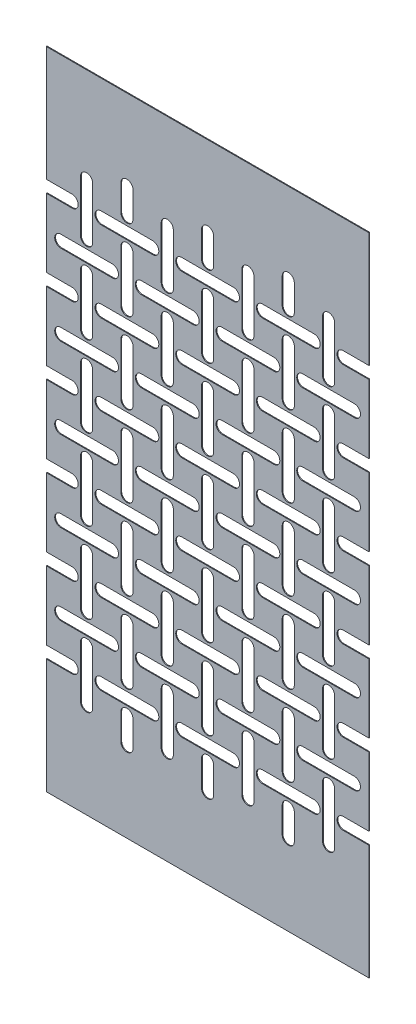
SolidWorks part; units mm, degrees
material "Kapton"
ref_plane "Front Plane" through (0, 0, 0) normal (0, 0, 1) x (1, 0, 0)
ref_plane "Top Plane" through (0, 0, 0) normal (0, 1, 0) x (1, 0, 0)
ref_plane "Right Plane" through (0, 0, 0) normal (1, 0, 0) x (0, 0, -1)
sketch "Model" plane through (0, 0, 0) normal (0, 0, 1) x (1, 0, 0)
  line L0 (0, 31.5) -> (6.4031, 31.5)
  line L1 (0, 28.5) -> (6.4031, 28.5)
  line L2 (13.5969, 31.5) -> (26.4031, 31.5)
  line L3 (13.5969, 28.5) -> (26.4031, 28.5)
  line L4 (33.5969, 31.5) -> (46.4031, 31.5)
  line L5 (33.5969, 28.5) -> (46.4031, 28.5)
  line L6 (53.5969, 31.5) -> (66.4031, 31.5)
  line L7 (53.5969, 28.5) -> (66.4031, 28.5)
  line L8 (73.5969, 31.5) -> (80, 31.5)
  line L9 (73.5969, 28.5) -> (80, 28.5)
  line L10 (3.5969, 41.5) -> (16.4031, 41.5)
  line L11 (3.5969, 38.5) -> (16.4031, 38.5)
  line L12 (23.5969, 41.5) -> (36.4031, 41.5)
  line L13 (23.5969, 38.5) -> (36.4031, 38.5)
  line L14 (43.5969, 41.5) -> (56.4031, 41.5)
  line L15 (43.5969, 38.5) -> (56.4031, 38.5)
  line L16 (63.5969, 41.5) -> (76.4031, 41.5)
  line L17 (63.5969, 38.5) -> (76.4031, 38.5)
  line L18 (0, 51.5) -> (6.4031, 51.5)
  line L19 (0, 48.5) -> (6.4031, 48.5)
  line L20 (13.5969, 51.5) -> (26.4031, 51.5)
  line L21 (13.5969, 48.5) -> (26.4031, 48.5)
  line L22 (33.5969, 51.5) -> (46.4031, 51.5)
  line L23 (33.5969, 48.5) -> (46.4031, 48.5)
  line L24 (53.5969, 51.5) -> (66.4031, 51.5)
  line L25 (53.5969, 48.5) -> (66.4031, 48.5)
  line L26 (73.5969, 51.5) -> (80, 51.5)
  line L27 (73.5969, 48.5) -> (80, 48.5)
  line L28 (3.5969, 61.5) -> (16.4031, 61.5)
  line L29 (3.5969, 58.5) -> (16.4031, 58.5)
  line L30 (23.5969, 61.5) -> (36.4031, 61.5)
  line L31 (23.5969, 58.5) -> (36.4031, 58.5)
  line L32 (43.5969, 61.5) -> (56.4031, 61.5)
  line L33 (43.5969, 58.5) -> (56.4031, 58.5)
  line L34 (63.5969, 61.5) -> (76.4031, 61.5)
  line L35 (63.5969, 58.5) -> (76.4031, 58.5)
  line L36 (0, 71.5) -> (6.4031, 71.5)
  line L37 (0, 68.5) -> (6.4031, 68.5)
  line L38 (13.5969, 71.5) -> (26.4031, 71.5)
  line L39 (13.5969, 68.5) -> (26.4031, 68.5)
  line L40 (33.5969, 71.5) -> (46.4031, 71.5)
  line L41 (33.5969, 68.5) -> (46.4031, 68.5)
  line L42 (53.5969, 71.5) -> (66.4031, 71.5)
  line L43 (53.5969, 68.5) -> (66.4031, 68.5)
  line L44 (73.5969, 71.5) -> (80, 71.5)
  line L45 (73.5969, 68.5) -> (80, 68.5)
  line L46 (3.5969, 81.5) -> (16.4031, 81.5)
  line L47 (3.5969, 78.5) -> (16.4031, 78.5)
  line L48 (23.5969, 81.5) -> (36.4031, 81.5)
  line L49 (23.5969, 78.5) -> (36.4031, 78.5)
  line L50 (43.5969, 81.5) -> (56.4031, 81.5)
  line L51 (43.5969, 78.5) -> (56.4031, 78.5)
  line L52 (63.5969, 81.5) -> (76.4031, 81.5)
  line L53 (63.5969, 78.5) -> (76.4031, 78.5)
  line L54 (0, 91.5) -> (6.4031, 91.5)
  line L55 (0, 88.5) -> (6.4031, 88.5)
  line L56 (13.5969, 91.5) -> (26.4031, 91.5)
  line L57 (13.5969, 88.5) -> (26.4031, 88.5)
  line L58 (33.5969, 91.5) -> (46.4031, 91.5)
  line L59 (33.5969, 88.5) -> (46.4031, 88.5)
  line L60 (53.5969, 91.5) -> (66.4031, 91.5)
  line L61 (53.5969, 88.5) -> (66.4031, 88.5)
  line L62 (73.5969, 91.5) -> (80, 91.5)
  line L63 (73.5969, 88.5) -> (80, 88.5)
  line L64 (3.5969, 101.5) -> (16.4031, 101.5)
  line L65 (3.5969, 98.5) -> (16.4031, 98.5)
  line L66 (23.5969, 101.5) -> (36.4031, 101.5)
  line L67 (23.5969, 98.5) -> (36.4031, 98.5)
  line L68 (43.5969, 101.5) -> (56.4031, 101.5)
  line L69 (43.5969, 98.5) -> (56.4031, 98.5)
  line L70 (63.5969, 101.5) -> (76.4031, 101.5)
  line L71 (63.5969, 98.5) -> (76.4031, 98.5)
  line L72 (0, 111.5) -> (6.4031, 111.5)
  line L73 (0, 108.5) -> (6.4031, 108.5)
  line L74 (13.5969, 111.5) -> (26.4031, 111.5)
  line L75 (13.5969, 108.5) -> (26.4031, 108.5)
  line L76 (33.5969, 111.5) -> (46.4031, 111.5)
  line L77 (33.5969, 108.5) -> (46.4031, 108.5)
  line L78 (53.5969, 111.5) -> (66.4031, 111.5)
  line L79 (53.5969, 108.5) -> (66.4031, 108.5)
  line L80 (73.5969, 111.5) -> (80, 111.5)
  line L81 (73.5969, 108.5) -> (80, 108.5)
  line L82 (3.5969, 121.5) -> (16.4031, 121.5)
  line L83 (3.5969, 118.5) -> (16.4031, 118.5)
  line L84 (23.5969, 121.5) -> (36.4031, 121.5)
  line L85 (23.5969, 118.5) -> (36.4031, 118.5)
  line L86 (43.5969, 121.5) -> (56.4031, 121.5)
  line L87 (43.5969, 118.5) -> (56.4031, 118.5)
  line L88 (63.5969, 121.5) -> (76.4031, 121.5)
  line L89 (63.5969, 118.5) -> (76.4031, 118.5)
  line L90 (0, 131.5) -> (6.4031, 131.5)
  line L91 (0, 128.5) -> (6.4031, 128.5)
  line L92 (13.5969, 131.5) -> (26.4031, 131.5)
  line L93 (13.5969, 128.5) -> (26.4031, 128.5)
  line L94 (33.5969, 131.5) -> (46.4031, 131.5)
  line L95 (33.5969, 128.5) -> (46.4031, 128.5)
  line L96 (53.5969, 131.5) -> (66.4031, 131.5)
  line L97 (53.5969, 128.5) -> (66.4031, 128.5)
  line L98 (73.5969, 131.5) -> (80, 131.5)
  line L99 (73.5969, 128.5) -> (80, 128.5)
  line L100 (11.5, 23.5969) -> (11.5, 36.4031)
  line L101 (8.5, 23.5969) -> (8.5, 36.4031)
  line L102 (11.5, 43.5969) -> (11.5, 56.4031)
  line L103 (8.5, 43.5969) -> (8.5, 56.4031)
  line L104 (11.5, 63.5969) -> (11.5, 76.4031)
  line L105 (8.5, 63.5969) -> (8.5, 76.4031)
  line L106 (11.5, 83.5969) -> (11.5, 96.4031)
  line L107 (8.5, 83.5969) -> (8.5, 96.4031)
  line L108 (11.5, 103.5969) -> (11.5, 116.4031)
  line L109 (8.5, 103.5969) -> (8.5, 116.4031)
  line L110 (11.5, 123.5969) -> (11.5, 136.4031)
  line L111 (8.5, 123.5969) -> (8.5, 136.4031)
  line L112 (21.5, 20) -> (21.5, 26.4031)
  line L113 (18.5, 20) -> (18.5, 26.4031)
  line L114 (21.5, 33.5969) -> (21.5, 46.4031)
  line L115 (18.5, 33.5969) -> (18.5, 46.4031)
  line L116 (21.5, 53.5969) -> (21.5, 66.4031)
  line L117 (18.5, 53.5969) -> (18.5, 66.4031)
  line L118 (21.5, 73.5969) -> (21.5, 86.4031)
  line L119 (18.5, 73.5969) -> (18.5, 86.4031)
  line L120 (21.5, 93.5969) -> (21.5, 106.4031)
  line L121 (18.5, 93.5969) -> (18.5, 106.4031)
  line L122 (21.5, 113.5969) -> (21.5, 126.4031)
  line L123 (18.5, 113.5969) -> (18.5, 126.4031)
  line L124 (21.5, 133.5969) -> (21.5, 140)
  line L125 (18.5, 133.5969) -> (18.5, 140)
  line L126 (31.5, 23.5969) -> (31.5, 36.4031)
  line L127 (28.5, 23.5969) -> (28.5, 36.4031)
  line L128 (31.5, 43.5969) -> (31.5, 56.4031)
  line L129 (28.5, 43.5969) -> (28.5, 56.4031)
  line L130 (31.5, 63.5969) -> (31.5, 76.4031)
  line L131 (28.5, 63.5969) -> (28.5, 76.4031)
  line L132 (31.5, 83.5969) -> (31.5, 96.4031)
  line L133 (28.5, 83.5969) -> (28.5, 96.4031)
  line L134 (31.5, 103.5969) -> (31.5, 116.4031)
  line L135 (28.5, 103.5969) -> (28.5, 116.4031)
  line L136 (31.5, 123.5969) -> (31.5, 136.4031)
  line L137 (28.5, 123.5969) -> (28.5, 136.4031)
  line L138 (41.5, 20) -> (41.5, 26.4031)
  line L139 (38.5, 20) -> (38.5, 26.4031)
  line L140 (41.5, 33.5969) -> (41.5, 46.4031)
  line L141 (38.5, 33.5969) -> (38.5, 46.4031)
  line L142 (41.5, 53.5969) -> (41.5, 66.4031)
  line L143 (38.5, 53.5969) -> (38.5, 66.4031)
  line L144 (41.5, 73.5969) -> (41.5, 86.4031)
  line L145 (38.5, 73.5969) -> (38.5, 86.4031)
  line L146 (41.5, 93.5969) -> (41.5, 106.4031)
  line L147 (38.5, 93.5969) -> (38.5, 106.4031)
  line L148 (41.5, 113.5969) -> (41.5, 126.4031)
  line L149 (38.5, 113.5969) -> (38.5, 126.4031)
  line L150 (41.5, 133.5969) -> (41.5, 140)
  line L151 (38.5, 133.5969) -> (38.5, 140)
  line L152 (51.5, 23.5969) -> (51.5, 36.4031)
  line L153 (48.5, 23.5969) -> (48.5, 36.4031)
  line L154 (51.5, 43.5969) -> (51.5, 56.4031)
  line L155 (48.5, 43.5969) -> (48.5, 56.4031)
  line L156 (51.5, 63.5969) -> (51.5, 76.4031)
  line L157 (48.5, 63.5969) -> (48.5, 76.4031)
  line L158 (51.5, 83.5969) -> (51.5, 96.4031)
  line L159 (48.5, 83.5969) -> (48.5, 96.4031)
  line L160 (51.5, 103.5969) -> (51.5, 116.4031)
  line L161 (48.5, 103.5969) -> (48.5, 116.4031)
  line L162 (51.5, 123.5969) -> (51.5, 136.4031)
  line L163 (48.5, 123.5969) -> (48.5, 136.4031)
  line L164 (61.5, 20) -> (61.5, 26.4031)
  line L165 (58.5, 20) -> (58.5, 26.4031)
  line L166 (61.5, 33.5969) -> (61.5, 46.4031)
  line L167 (58.5, 33.5969) -> (58.5, 46.4031)
  line L168 (61.5, 53.5969) -> (61.5, 66.4031)
  line L169 (58.5, 53.5969) -> (58.5, 66.4031)
  line L170 (61.5, 73.5969) -> (61.5, 86.4031)
  line L171 (58.5, 73.5969) -> (58.5, 86.4031)
  line L172 (61.5, 93.5969) -> (61.5, 106.4031)
  line L173 (58.5, 93.5969) -> (58.5, 106.4031)
  line L174 (61.5, 113.5969) -> (61.5, 126.4031)
  line L175 (58.5, 113.5969) -> (58.5, 126.4031)
  line L176 (61.5, 133.5969) -> (61.5, 140)
  line L177 (58.5, 133.5969) -> (58.5, 140)
  line L178 (71.5, 23.5969) -> (71.5, 36.4031)
  line L179 (68.5, 23.5969) -> (68.5, 36.4031)
  line L180 (71.5, 43.5969) -> (71.5, 56.4031)
  line L181 (68.5, 43.5969) -> (68.5, 56.4031)
  line L182 (71.5, 63.5969) -> (71.5, 76.4031)
  line L183 (68.5, 63.5969) -> (68.5, 76.4031)
  line L184 (71.5, 83.5969) -> (71.5, 96.4031)
  line L185 (68.5, 83.5969) -> (68.5, 96.4031)
  line L186 (71.5, 103.5969) -> (71.5, 116.4031)
  line L187 (68.5, 103.5969) -> (68.5, 116.4031)
  line L188 (71.5, 123.5969) -> (71.5, 136.4031)
  line L189 (68.5, 123.5969) -> (68.5, 136.4031)
  line L190 (0, 0) -> (80, 0)
  line L191 (80, 0) -> (80, 28.5)
  line L192 (80, 31.5) -> (80, 48.5)
  line L193 (80, 51.5) -> (80, 68.5)
  line L194 (80, 71.5) -> (80, 88.5)
  line L195 (80, 91.5) -> (80, 108.5)
  line L196 (80, 111.5) -> (80, 128.5)
  line L197 (80, 131.5) -> (80, 160)
  line L198 (80, 160) -> (0, 160)
  line L199 (0, 0) -> (0, 28.5)
  line L200 (0, 31.5) -> (0, 48.5)
  line L201 (0, 51.5) -> (0, 68.5)
  line L202 (0, 71.5) -> (0, 88.5)
  line L203 (0, 91.5) -> (0, 108.5)
  line L204 (0, 111.5) -> (0, 128.5)
  line L205 (0, 131.5) -> (0, 160)
  arc A0 (6.4031, 28.5) -> (6.4031, 31.5) centre (6.4031, 30) ccw
  arc A1 (13.5969, 31.5) -> (13.5969, 28.5) centre (13.5969, 30) ccw
  arc A2 (26.4031, 28.5) -> (26.4031, 31.5) centre (26.4031, 30) ccw
  arc A3 (33.5969, 31.5) -> (33.5969, 28.5) centre (33.5969, 30) ccw
  arc A4 (46.4031, 28.5) -> (46.4031, 31.5) centre (46.4031, 30) ccw
  arc A5 (53.5969, 31.5) -> (53.5969, 28.5) centre (53.5969, 30) ccw
  arc A6 (66.4031, 28.5) -> (66.4031, 31.5) centre (66.4031, 30) ccw
  arc A7 (73.5969, 31.5) -> (73.5969, 28.5) centre (73.5969, 30) ccw
  arc A8 (3.5969, 41.5) -> (3.5969, 38.5) centre (3.5969, 40) ccw
  arc A9 (16.4031, 38.5) -> (16.4031, 41.5) centre (16.4031, 40) ccw
  arc A10 (23.5969, 41.5) -> (23.5969, 38.5) centre (23.5969, 40) ccw
  arc A11 (36.4031, 38.5) -> (36.4031, 41.5) centre (36.4031, 40) ccw
  arc A12 (43.5969, 41.5) -> (43.5969, 38.5) centre (43.5969, 40) ccw
  arc A13 (56.4031, 38.5) -> (56.4031, 41.5) centre (56.4031, 40) ccw
  arc A14 (63.5969, 41.5) -> (63.5969, 38.5) centre (63.5969, 40) ccw
  arc A15 (76.4031, 38.5) -> (76.4031, 41.5) centre (76.4031, 40) ccw
  arc A16 (6.4031, 48.5) -> (6.4031, 51.5) centre (6.4031, 50) ccw
  arc A17 (13.5969, 51.5) -> (13.5969, 48.5) centre (13.5969, 50) ccw
  arc A18 (26.4031, 48.5) -> (26.4031, 51.5) centre (26.4031, 50) ccw
  arc A19 (33.5969, 51.5) -> (33.5969, 48.5) centre (33.5969, 50) ccw
  arc A20 (46.4031, 48.5) -> (46.4031, 51.5) centre (46.4031, 50) ccw
  arc A21 (53.5969, 51.5) -> (53.5969, 48.5) centre (53.5969, 50) ccw
  arc A22 (66.4031, 48.5) -> (66.4031, 51.5) centre (66.4031, 50) ccw
  arc A23 (73.5969, 51.5) -> (73.5969, 48.5) centre (73.5969, 50) ccw
  arc A24 (3.5969, 61.5) -> (3.5969, 58.5) centre (3.5969, 60) ccw
  arc A25 (16.4031, 58.5) -> (16.4031, 61.5) centre (16.4031, 60) ccw
  arc A26 (23.5969, 61.5) -> (23.5969, 58.5) centre (23.5969, 60) ccw
  arc A27 (36.4031, 58.5) -> (36.4031, 61.5) centre (36.4031, 60) ccw
  arc A28 (43.5969, 61.5) -> (43.5969, 58.5) centre (43.5969, 60) ccw
  arc A29 (56.4031, 58.5) -> (56.4031, 61.5) centre (56.4031, 60) ccw
  arc A30 (63.5969, 61.5) -> (63.5969, 58.5) centre (63.5969, 60) ccw
  arc A31 (76.4031, 58.5) -> (76.4031, 61.5) centre (76.4031, 60) ccw
  arc A32 (6.4031, 68.5) -> (6.4031, 71.5) centre (6.4031, 70) ccw
  arc A33 (13.5969, 71.5) -> (13.5969, 68.5) centre (13.5969, 70) ccw
  arc A34 (26.4031, 68.5) -> (26.4031, 71.5) centre (26.4031, 70) ccw
  arc A35 (33.5969, 71.5) -> (33.5969, 68.5) centre (33.5969, 70) ccw
  arc A36 (46.4031, 68.5) -> (46.4031, 71.5) centre (46.4031, 70) ccw
  arc A37 (53.5969, 71.5) -> (53.5969, 68.5) centre (53.5969, 70) ccw
  arc A38 (66.4031, 68.5) -> (66.4031, 71.5) centre (66.4031, 70) ccw
  arc A39 (73.5969, 71.5) -> (73.5969, 68.5) centre (73.5969, 70) ccw
  arc A40 (3.5969, 81.5) -> (3.5969, 78.5) centre (3.5969, 80) ccw
  arc A41 (16.4031, 78.5) -> (16.4031, 81.5) centre (16.4031, 80) ccw
  arc A42 (23.5969, 81.5) -> (23.5969, 78.5) centre (23.5969, 80) ccw
  arc A43 (36.4031, 78.5) -> (36.4031, 81.5) centre (36.4031, 80) ccw
  arc A44 (43.5969, 81.5) -> (43.5969, 78.5) centre (43.5969, 80) ccw
  arc A45 (56.4031, 78.5) -> (56.4031, 81.5) centre (56.4031, 80) ccw
  arc A46 (63.5969, 81.5) -> (63.5969, 78.5) centre (63.5969, 80) ccw
  arc A47 (76.4031, 78.5) -> (76.4031, 81.5) centre (76.4031, 80) ccw
  arc A48 (6.4031, 88.5) -> (6.4031, 91.5) centre (6.4031, 90) ccw
  arc A49 (13.5969, 91.5) -> (13.5969, 88.5) centre (13.5969, 90) ccw
  arc A50 (26.4031, 88.5) -> (26.4031, 91.5) centre (26.4031, 90) ccw
  arc A51 (33.5969, 91.5) -> (33.5969, 88.5) centre (33.5969, 90) ccw
  arc A52 (46.4031, 88.5) -> (46.4031, 91.5) centre (46.4031, 90) ccw
  arc A53 (53.5969, 91.5) -> (53.5969, 88.5) centre (53.5969, 90) ccw
  arc A54 (66.4031, 88.5) -> (66.4031, 91.5) centre (66.4031, 90) ccw
  arc A55 (73.5969, 91.5) -> (73.5969, 88.5) centre (73.5969, 90) ccw
  arc A56 (3.5969, 101.5) -> (3.5969, 98.5) centre (3.5969, 100) ccw
  arc A57 (16.4031, 98.5) -> (16.4031, 101.5) centre (16.4031, 100) ccw
  arc A58 (23.5969, 101.5) -> (23.5969, 98.5) centre (23.5969, 100) ccw
  arc A59 (36.4031, 98.5) -> (36.4031, 101.5) centre (36.4031, 100) ccw
  arc A60 (43.5969, 101.5) -> (43.5969, 98.5) centre (43.5969, 100) ccw
  arc A61 (56.4031, 98.5) -> (56.4031, 101.5) centre (56.4031, 100) ccw
  arc A62 (63.5969, 101.5) -> (63.5969, 98.5) centre (63.5969, 100) ccw
  arc A63 (76.4031, 98.5) -> (76.4031, 101.5) centre (76.4031, 100) ccw
  arc A64 (6.4031, 108.5) -> (6.4031, 111.5) centre (6.4031, 110) ccw
  arc A65 (13.5969, 111.5) -> (13.5969, 108.5) centre (13.5969, 110) ccw
  arc A66 (26.4031, 108.5) -> (26.4031, 111.5) centre (26.4031, 110) ccw
  arc A67 (33.5969, 111.5) -> (33.5969, 108.5) centre (33.5969, 110) ccw
  arc A68 (46.4031, 108.5) -> (46.4031, 111.5) centre (46.4031, 110) ccw
  arc A69 (53.5969, 111.5) -> (53.5969, 108.5) centre (53.5969, 110) ccw
  arc A70 (66.4031, 108.5) -> (66.4031, 111.5) centre (66.4031, 110) ccw
  arc A71 (73.5969, 111.5) -> (73.5969, 108.5) centre (73.5969, 110) ccw
  arc A72 (3.5969, 121.5) -> (3.5969, 118.5) centre (3.5969, 120) ccw
  arc A73 (16.4031, 118.5) -> (16.4031, 121.5) centre (16.4031, 120) ccw
  arc A74 (23.5969, 121.5) -> (23.5969, 118.5) centre (23.5969, 120) ccw
  arc A75 (36.4031, 118.5) -> (36.4031, 121.5) centre (36.4031, 120) ccw
  arc A76 (43.5969, 121.5) -> (43.5969, 118.5) centre (43.5969, 120) ccw
  arc A77 (56.4031, 118.5) -> (56.4031, 121.5) centre (56.4031, 120) ccw
  arc A78 (63.5969, 121.5) -> (63.5969, 118.5) centre (63.5969, 120) ccw
  arc A79 (76.4031, 118.5) -> (76.4031, 121.5) centre (76.4031, 120) ccw
  arc A80 (6.4031, 128.5) -> (6.4031, 131.5) centre (6.4031, 130) ccw
  arc A81 (13.5969, 131.5) -> (13.5969, 128.5) centre (13.5969, 130) ccw
  arc A82 (26.4031, 128.5) -> (26.4031, 131.5) centre (26.4031, 130) ccw
  arc A83 (33.5969, 131.5) -> (33.5969, 128.5) centre (33.5969, 130) ccw
  arc A84 (46.4031, 128.5) -> (46.4031, 131.5) centre (46.4031, 130) ccw
  arc A85 (53.5969, 131.5) -> (53.5969, 128.5) centre (53.5969, 130) ccw
  arc A86 (66.4031, 128.5) -> (66.4031, 131.5) centre (66.4031, 130) ccw
  arc A87 (73.5969, 131.5) -> (73.5969, 128.5) centre (73.5969, 130) ccw
  arc A88 (8.5, 23.5969) -> (11.5, 23.5969) centre (10, 23.5969) ccw
  arc A89 (11.5, 36.4031) -> (8.5, 36.4031) centre (10, 36.4031) ccw
  arc A90 (8.5, 43.5969) -> (11.5, 43.5969) centre (10, 43.5969) ccw
  arc A91 (11.5, 56.4031) -> (8.5, 56.4031) centre (10, 56.4031) ccw
  arc A92 (8.5, 63.5969) -> (11.5, 63.5969) centre (10, 63.5969) ccw
  arc A93 (11.5, 76.4031) -> (8.5, 76.4031) centre (10, 76.4031) ccw
  arc A94 (8.5, 83.5969) -> (11.5, 83.5969) centre (10, 83.5969) ccw
  arc A95 (11.5, 96.4031) -> (8.5, 96.4031) centre (10, 96.4031) ccw
  arc A96 (8.5, 103.5969) -> (11.5, 103.5969) centre (10, 103.5969) ccw
  arc A97 (11.5, 116.4031) -> (8.5, 116.4031) centre (10, 116.4031) ccw
  arc A98 (8.5, 123.5969) -> (11.5, 123.5969) centre (10, 123.5969) ccw
  arc A99 (11.5, 136.4031) -> (8.5, 136.4031) centre (10, 136.4031) ccw
  arc A100 (18.5, 20) -> (21.5, 20) centre (20, 20) ccw
  arc A101 (21.5, 26.4031) -> (18.5, 26.4031) centre (20, 26.4031) ccw
  arc A102 (18.5, 33.5969) -> (21.5, 33.5969) centre (20, 33.5969) ccw
  arc A103 (21.5, 46.4031) -> (18.5, 46.4031) centre (20, 46.4031) ccw
  arc A104 (18.5, 53.5969) -> (21.5, 53.5969) centre (20, 53.5969) ccw
  arc A105 (21.5, 66.4031) -> (18.5, 66.4031) centre (20, 66.4031) ccw
  arc A106 (18.5, 73.5969) -> (21.5, 73.5969) centre (20, 73.5969) ccw
  arc A107 (21.5, 86.4031) -> (18.5, 86.4031) centre (20, 86.4031) ccw
  arc A108 (18.5, 93.5969) -> (21.5, 93.5969) centre (20, 93.5969) ccw
  arc A109 (21.5, 106.4031) -> (18.5, 106.4031) centre (20, 106.4031) ccw
  arc A110 (18.5, 113.5969) -> (21.5, 113.5969) centre (20, 113.5969) ccw
  arc A111 (21.5, 126.4031) -> (18.5, 126.4031) centre (20, 126.4031) ccw
  arc A112 (18.5, 133.5969) -> (21.5, 133.5969) centre (20, 133.5969) ccw
  arc A113 (21.5, 140) -> (18.5, 140) centre (20, 140) ccw
  arc A114 (28.5, 23.5969) -> (31.5, 23.5969) centre (30, 23.5969) ccw
  arc A115 (31.5, 36.4031) -> (28.5, 36.4031) centre (30, 36.4031) ccw
  arc A116 (28.5, 43.5969) -> (31.5, 43.5969) centre (30, 43.5969) ccw
  arc A117 (31.5, 56.4031) -> (28.5, 56.4031) centre (30, 56.4031) ccw
  arc A118 (28.5, 63.5969) -> (31.5, 63.5969) centre (30, 63.5969) ccw
  arc A119 (31.5, 76.4031) -> (28.5, 76.4031) centre (30, 76.4031) ccw
  arc A120 (28.5, 83.5969) -> (31.5, 83.5969) centre (30, 83.5969) ccw
  arc A121 (31.5, 96.4031) -> (28.5, 96.4031) centre (30, 96.4031) ccw
  arc A122 (28.5, 103.5969) -> (31.5, 103.5969) centre (30, 103.5969) ccw
  arc A123 (31.5, 116.4031) -> (28.5, 116.4031) centre (30, 116.4031) ccw
  arc A124 (28.5, 123.5969) -> (31.5, 123.5969) centre (30, 123.5969) ccw
  arc A125 (31.5, 136.4031) -> (28.5, 136.4031) centre (30, 136.4031) ccw
  arc A126 (38.5, 20) -> (41.5, 20) centre (40, 20) ccw
  arc A127 (41.5, 26.4031) -> (38.5, 26.4031) centre (40, 26.4031) ccw
  arc A128 (38.5, 33.5969) -> (41.5, 33.5969) centre (40, 33.5969) ccw
  arc A129 (41.5, 46.4031) -> (38.5, 46.4031) centre (40, 46.4031) ccw
  arc A130 (38.5, 53.5969) -> (41.5, 53.5969) centre (40, 53.5969) ccw
  arc A131 (41.5, 66.4031) -> (38.5, 66.4031) centre (40, 66.4031) ccw
  arc A132 (38.5, 73.5969) -> (41.5, 73.5969) centre (40, 73.5969) ccw
  arc A133 (41.5, 86.4031) -> (38.5, 86.4031) centre (40, 86.4031) ccw
  arc A134 (38.5, 93.5969) -> (41.5, 93.5969) centre (40, 93.5969) ccw
  arc A135 (41.5, 106.4031) -> (38.5, 106.4031) centre (40, 106.4031) ccw
  arc A136 (38.5, 113.5969) -> (41.5, 113.5969) centre (40, 113.5969) ccw
  arc A137 (41.5, 126.4031) -> (38.5, 126.4031) centre (40, 126.4031) ccw
  arc A138 (38.5, 133.5969) -> (41.5, 133.5969) centre (40, 133.5969) ccw
  arc A139 (41.5, 140) -> (38.5, 140) centre (40, 140) ccw
  arc A140 (48.5, 23.5969) -> (51.5, 23.5969) centre (50, 23.5969) ccw
  arc A141 (51.5, 36.4031) -> (48.5, 36.4031) centre (50, 36.4031) ccw
  arc A142 (48.5, 43.5969) -> (51.5, 43.5969) centre (50, 43.5969) ccw
  arc A143 (51.5, 56.4031) -> (48.5, 56.4031) centre (50, 56.4031) ccw
  arc A144 (48.5, 63.5969) -> (51.5, 63.5969) centre (50, 63.5969) ccw
  arc A145 (51.5, 76.4031) -> (48.5, 76.4031) centre (50, 76.4031) ccw
  arc A146 (48.5, 83.5969) -> (51.5, 83.5969) centre (50, 83.5969) ccw
  arc A147 (51.5, 96.4031) -> (48.5, 96.4031) centre (50, 96.4031) ccw
  arc A148 (48.5, 103.5969) -> (51.5, 103.5969) centre (50, 103.5969) ccw
  arc A149 (51.5, 116.4031) -> (48.5, 116.4031) centre (50, 116.4031) ccw
  arc A150 (48.5, 123.5969) -> (51.5, 123.5969) centre (50, 123.5969) ccw
  arc A151 (51.5, 136.4031) -> (48.5, 136.4031) centre (50, 136.4031) ccw
  arc A152 (58.5, 20) -> (61.5, 20) centre (60, 20) ccw
  arc A153 (61.5, 26.4031) -> (58.5, 26.4031) centre (60, 26.4031) ccw
  arc A154 (58.5, 33.5969) -> (61.5, 33.5969) centre (60, 33.5969) ccw
  arc A155 (61.5, 46.4031) -> (58.5, 46.4031) centre (60, 46.4031) ccw
  arc A156 (58.5, 53.5969) -> (61.5, 53.5969) centre (60, 53.5969) ccw
  arc A157 (61.5, 66.4031) -> (58.5, 66.4031) centre (60, 66.4031) ccw
  arc A158 (58.5, 73.5969) -> (61.5, 73.5969) centre (60, 73.5969) ccw
  arc A159 (61.5, 86.4031) -> (58.5, 86.4031) centre (60, 86.4031) ccw
  arc A160 (58.5, 93.5969) -> (61.5, 93.5969) centre (60, 93.5969) ccw
  arc A161 (61.5, 106.4031) -> (58.5, 106.4031) centre (60, 106.4031) ccw
  arc A162 (58.5, 113.5969) -> (61.5, 113.5969) centre (60, 113.5969) ccw
  arc A163 (61.5, 126.4031) -> (58.5, 126.4031) centre (60, 126.4031) ccw
  arc A164 (58.5, 133.5969) -> (61.5, 133.5969) centre (60, 133.5969) ccw
  arc A165 (61.5, 140) -> (58.5, 140) centre (60, 140) ccw
  arc A166 (68.5, 23.5969) -> (71.5, 23.5969) centre (70, 23.5969) ccw
  arc A167 (71.5, 36.4031) -> (68.5, 36.4031) centre (70, 36.4031) ccw
  arc A168 (68.5, 43.5969) -> (71.5, 43.5969) centre (70, 43.5969) ccw
  arc A169 (71.5, 56.4031) -> (68.5, 56.4031) centre (70, 56.4031) ccw
  arc A170 (68.5, 63.5969) -> (71.5, 63.5969) centre (70, 63.5969) ccw
  arc A171 (71.5, 76.4031) -> (68.5, 76.4031) centre (70, 76.4031) ccw
  arc A172 (68.5, 83.5969) -> (71.5, 83.5969) centre (70, 83.5969) ccw
  arc A173 (71.5, 96.4031) -> (68.5, 96.4031) centre (70, 96.4031) ccw
  arc A174 (68.5, 103.5969) -> (71.5, 103.5969) centre (70, 103.5969) ccw
  arc A175 (71.5, 116.4031) -> (68.5, 116.4031) centre (70, 116.4031) ccw
  arc A176 (68.5, 123.5969) -> (71.5, 123.5969) centre (70, 123.5969) ccw
  arc A177 (71.5, 136.4031) -> (68.5, 136.4031) centre (70, 136.4031) ccw
extrude "Boss-Extrude1" add sketch "Model" along normal blind 0.2
